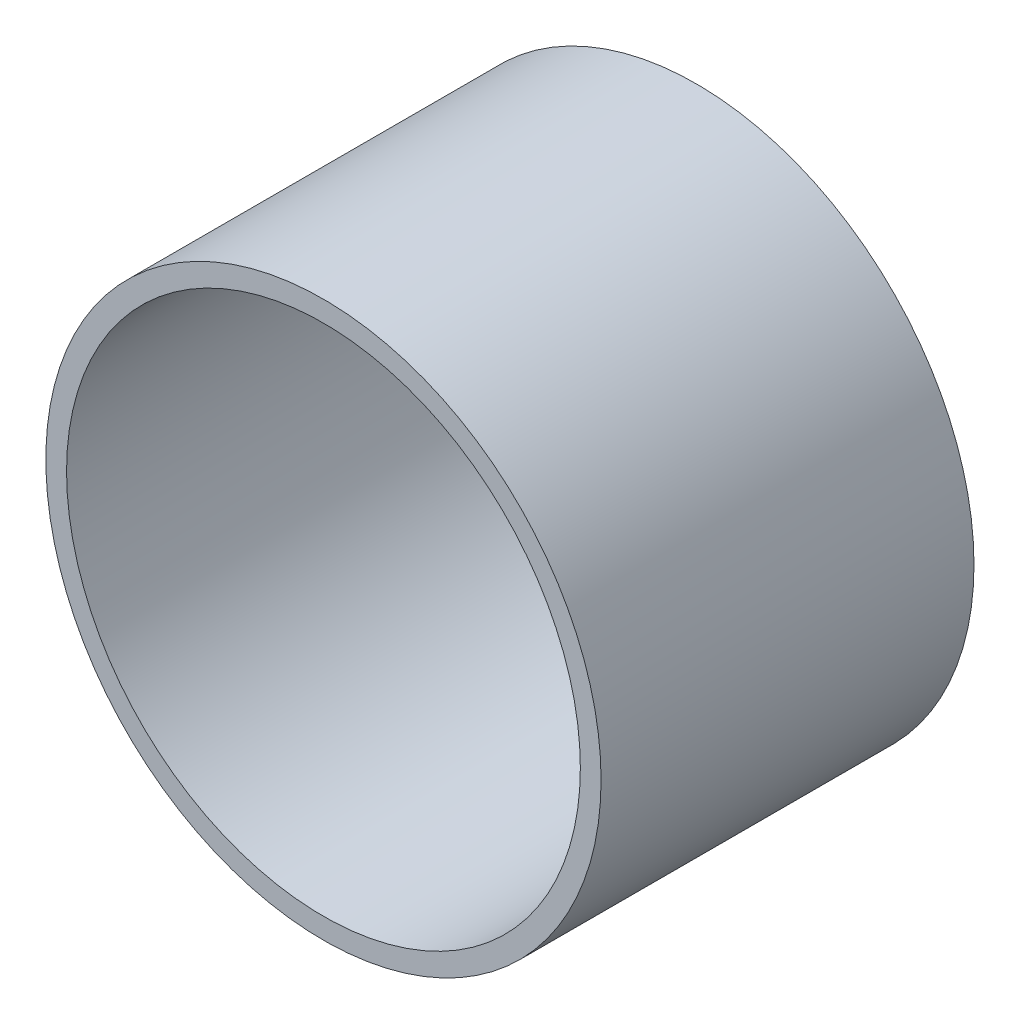
SolidWorks part; units mm, degrees
ref_plane "Front Plane" through (0, 0, 0) normal (0, 0, 1) x (1, 0, 0)
ref_plane "Top Plane" through (0, 0, 0) normal (0, 1, 0) x (1, 0, 0)
ref_plane "Right Plane" through (0, 0, 0) normal (1, 0, 0) x (0, 0, -1)
sketch "Sketch1" plane through (0, 0, 0) normal (0, 0, 1) x (1, 0, 0)
  circle A1 centre (0, 0) radius 31
  circle A2 centre (0, 0) radius 33.5
  circle A4 centre (0, 0) radius 31 construction
  circle A5 centre (0, 0) radius 32.5 construction
  dimension "D1" = 1
extrude "Boss-Extrude1" add sketch "Sketch1" against normal up to surface (45 mm away) from surface contours A2 A1
